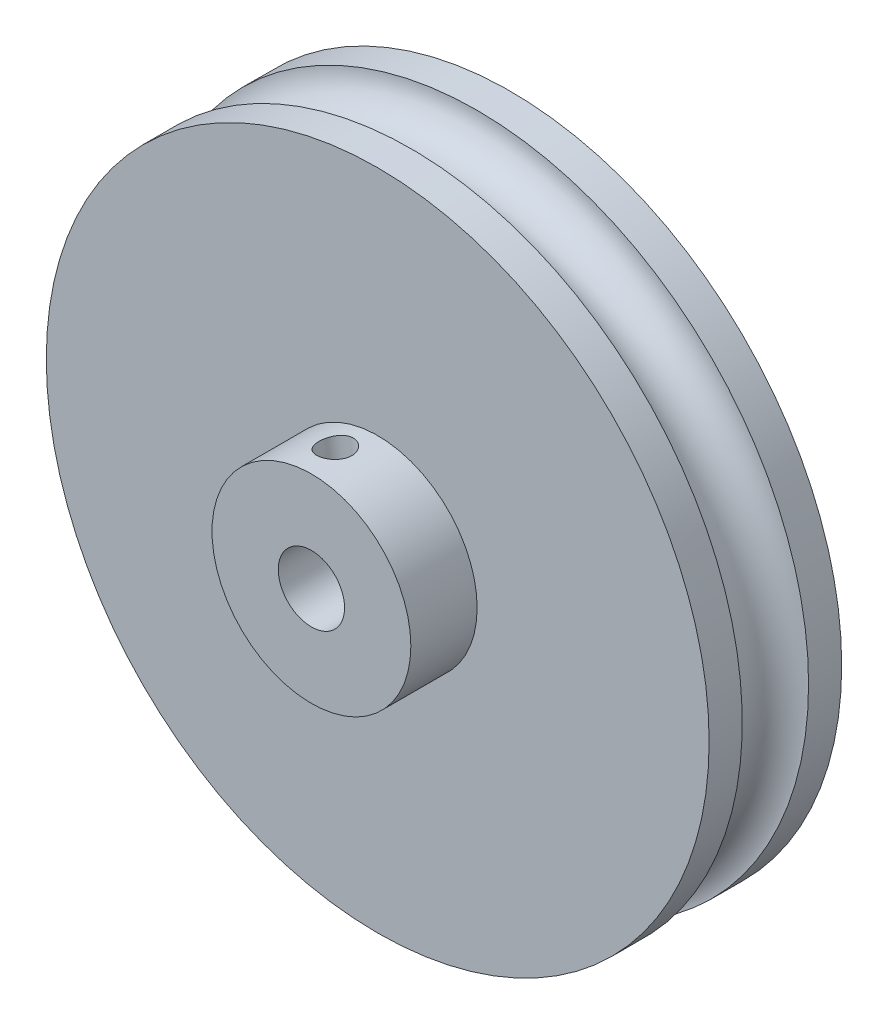
SolidWorks part; units mm, degrees
ref_plane "Plan de face" through (0, 0, 0) normal (0, 0, 1) x (1, 0, 0)
ref_plane "Plan de dessus" through (0, 0, 0) normal (0, 1, 0) x (1, 0, 0)
ref_plane "Plan de droite" through (0, 0, 0) normal (1, 0, 0) x (0, 0, -1)
sketch "Esquisse1" plane through (0, 0, 0) normal (0, 0, 1) x (1, 0, 0)
  circle A0 centre (0, 0) radius 25
  dimension "D1" = 50
extrude "Boss.-Extru.1" add sketch "Esquisse1" along normal blind 10
sketch "Esquisse2" plane through (0, 0, 0) normal (0, 1, 0) x (1, 0, 0)
  line L0 (-25, 0) -> (-25, -10) construction
  line L1 (0, 0) -> (0, -10) construction
  line L2 (-25, -10) -> (25, -10) construction
  circle A0 centre (-25, -5) radius 2.5
  dimension "D1" = 5
revolve "Enlèvement de matière-Révolution1" cut sketch "Esquisse2" angle 360 about L1
sketch "Esquisse5" plane through (0, 0, 10) normal (0, 0, 1) x (1, 0, 0)
  circle A0 centre (0, 0) radius 7.5
  dimension "D1" = 15
extrude "Boss.-Extru.3" add sketch "Esquisse5" along normal blind 5
sketch "Esquisse6" plane through (0, 0, 15) normal (0, 0, 1) x (1, 0, 0)
  circle A0 centre (0, 0) radius 2.5
  dimension "D1" = 5
extrude "Enlèv. mat.-Extru.2" cut sketch "Esquisse6" against normal through all
hole_wizard "Trou taraudé M31" positions "Esquisse3D1" profile "Esquisse7" tap size "M3" standard "ISO"
sketch3d "Esquisse3D1"
  point P0 (-0.9241, 7.4428, 12.2795)
  point P12 (-0.9273, 7.4425, 10)
  point P13 (-0.8825, 7.4479, 12.2014)
  point P14 (-0.9241, 7.4428, 12.2795)
sketch "Esquisse7" plane through (-0.9241, 7.4428, 12.2795) normal (0, 0, 1) x (-0.9924, -0.1232, 0)
  line L0 (0, 0) -> (0, 9.2511)
  line L1 (0, 9.2511) -> (1.25, 8.5)
  line L2 (1.25, 8.5) -> (1.25, 0)
  line L5 (1.25, 0) -> (0, 0)
  line L10 (0, 9.2511) -> (-1.25, 8.5) construction
  line L11 (0, -6.35) -> (0, 107.95) construction
  dimension "Diamètre du trou pour taraudage" = 2.5
  dimension "Profondeur du trou pour taraudage" = 8.5
  dimension "Angle de pointe" = 118
cosmetic thread "Filetage de perçage1" parameters "D1"=5.3349, "D2"=3
